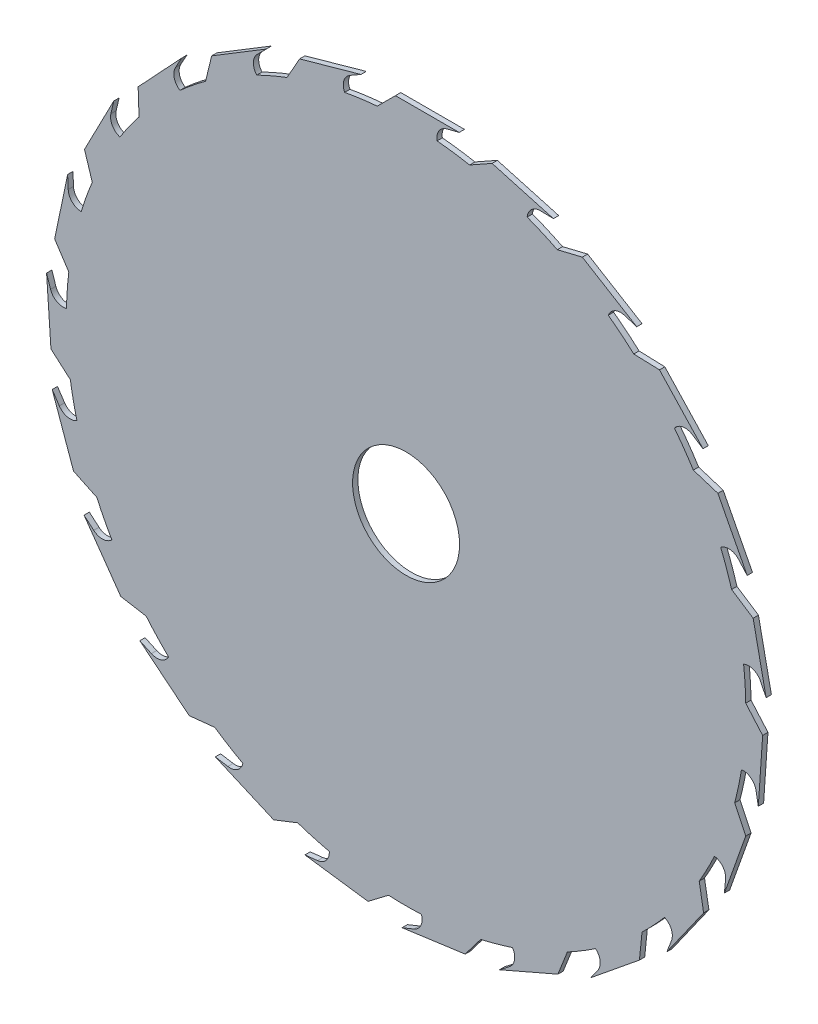
SolidWorks part; units mm, degrees
material "Chrome Stainless Steel"
ref_plane "Front Plane" through (0, 0, 0) normal (0, 0, 1) x (1, 0, 0)
ref_plane "Top Plane" through (0, 0, 0) normal (0, 1, 0) x (1, 0, 0)
ref_plane "Right Plane" through (0, 0, 0) normal (1, 0, 0) x (0, 0, -1)
sketch "Sketch1" plane through (0, 0, 0) normal (0, 0, 1) x (1, 0, 0)
  circle A0 centre (0, 0) radius 101.6
  dimension "D1" = 203.2
extrude "Boss-Extrude1" add sketch "Sketch1" along normal blind 1.5875 contours A0
sketch "Sketch2" plane through (0, 0, 1.5875) normal (0, 0, 1) x (1, 0, 0)
  circle A0 centre (0, 0) radius 16.002
  dimension "D1" = 32.004
extrude "Cut-Extrude1" cut sketch "Sketch2" against normal up to next
sketch "Sketch4" plane through (0, 0, 1.5875) normal (0, 0, 1) x (1, 0, 0)
  line L0 (-9.525, 100.33) -> (-3.175, 106.68)
  line L1 (-3.175, 106.68) -> (15.875, 106.68)
  line L2 (15.875, 106.68) -> (12.1813, 105.7459)
  line L3 (9.525, 100.33) -> (-9.525, 100.33)
  arc A0 (12.1813, 105.7459) -> (9.525, 100.33) centre (13.1512, 101.9108) ccw
  point P8 (0, 100.33)
  dimension "D1" = 3.81
  dimension "D7" = 1.5808
  dimension "D2" = 19.05
  dimension "D3" = 6.35
  dimension "D4" = 19.05
  dimension "D5" = 106.68
  dimension "D6" = 45
extrude "Boss-Extrude2" add sketch "Sketch4" against normal up to surface (1.5875 mm away) up to face at (16.002, 0, 0)
pattern_circular "CirPattern1" count 23 over 360 about axis through (0, 0, 0) along (0, 0, 1) of "Boss-Extrude2"
